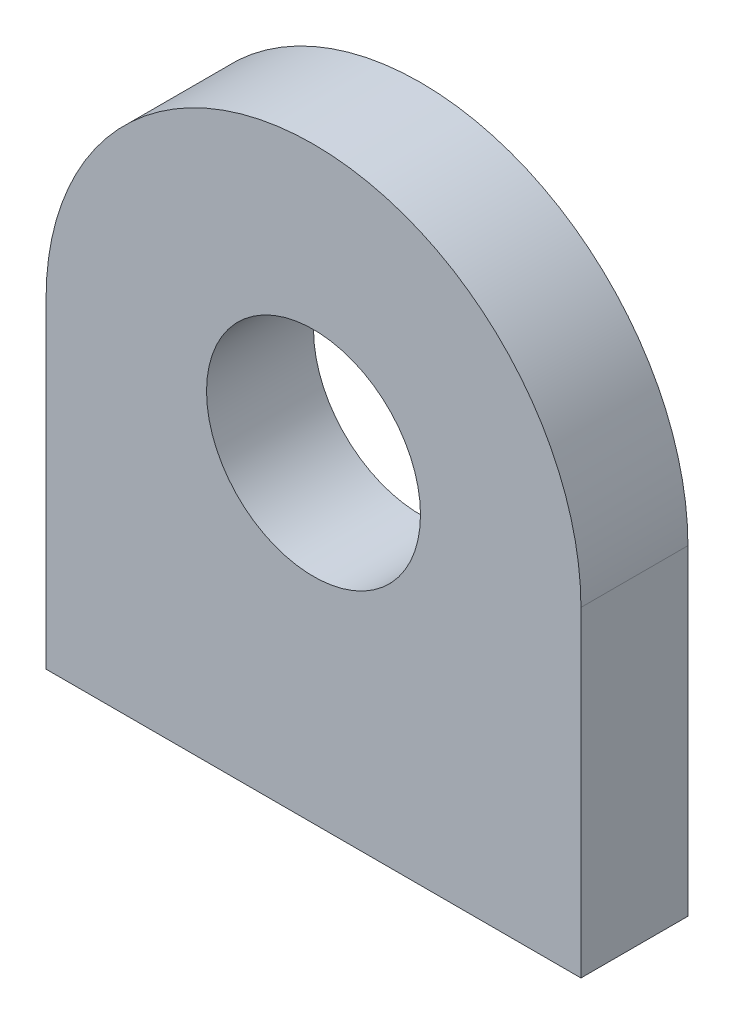
SolidWorks part; units mm, degrees
material "Plain Carbon Steel"
ref_plane "Front Plane" through (0, 0, 0) normal (0, 0, 1) x (1, 0, 0)
ref_plane "Top Plane" through (0, 0, 0) normal (0, 1, 0) x (1, 0, 0)
ref_plane "Right Plane" through (0, 0, 0) normal (1, 0, 0) x (0, 0, -1)
sketch "Sketch1" plane through (0, 0, 0) normal (0, 0, 1) x (1, 0, 0)
  line L0 (-25, 0) -> (-25, -30)
  line L1 (-25, -30) -> (25, -30)
  line L2 (25, -30) -> (25, 0)
  arc A0 (25, 0) -> (-25, 0) centre (0, 0) ccw
  dimension "D1" = 50
  dimension "D2" = 30
extrude "Boss-Extrude1" add sketch "Sketch1" along normal blind 10
sketch "Sketch2" plane through (0, 0, 10) normal (0, 0, 1) x (1, 0, 0)
  circle A0 centre (0, 0) radius 10
  dimension "D1" = 20
extrude "Cut-Extrude1" cut sketch "Sketch2" against normal blind 10
